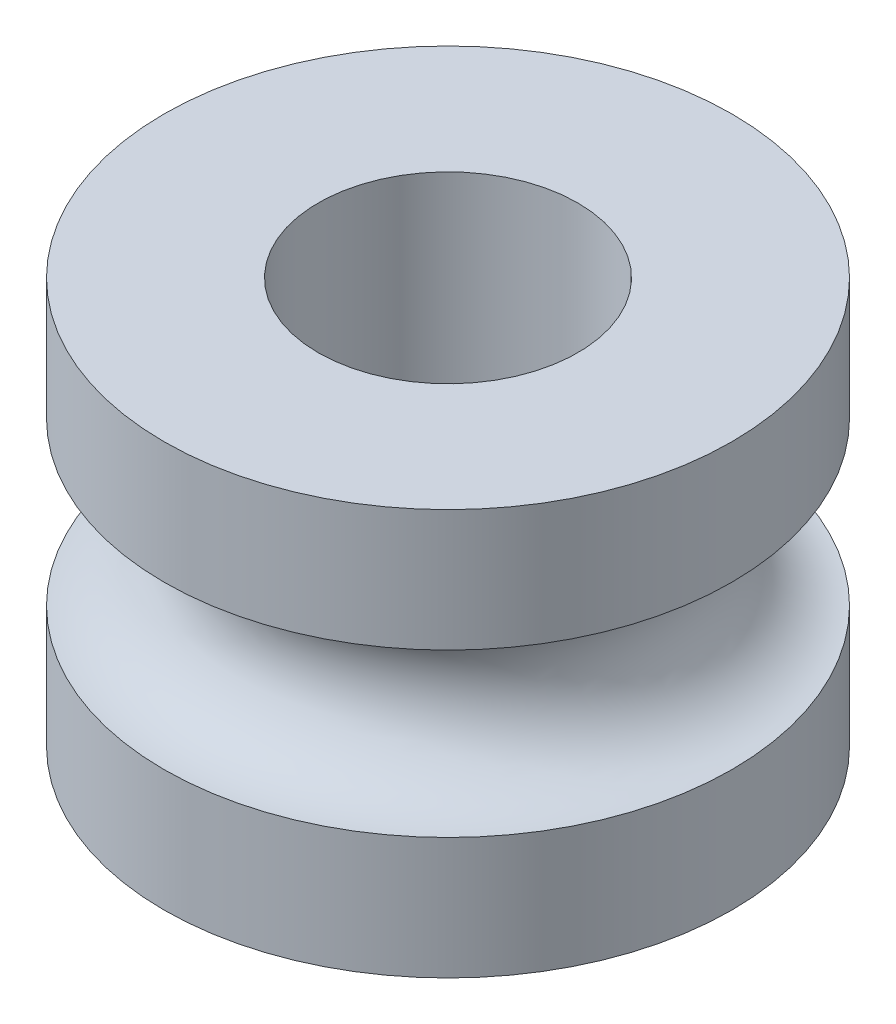
SolidWorks part; units mm, degrees
ref_plane "Front Plane" through (0, 0, 0) normal (0, 0, 1) x (1, 0, 0)
ref_plane "Top Plane" through (0, 0, 0) normal (0, 1, 0) x (1, 0, 0)
ref_plane "Right Plane" through (0, 0, 0) normal (1, 0, 0) x (0, 0, -1)
sketch "Sketch1" plane through (0, 0, 0) normal (0, 0, 1) x (1, 0, 0)
  line L0 (-1.6, 2.5) -> (-3.5, 2.5)
  line L1 (-3.5, 2.5) -> (-3.5, 1)
  line L2 (-3.5, -1) -> (-3.5, -2.5)
  line L3 (-3.5, -2.5) -> (-1.6, -2.5)
  line L4 (-1.6, -2.5) -> (-1.6, 2.5)
  arc A0 (-3.5, 1) -> (-3.5, -1) centre (-3.5, 0) cw
  dimension "D1" = 1
  dimension "D2" = 1.5
  dimension "D3" = 1.6
  dimension "D4" = 3.5
ref_axis "Axis1" through (0, 2.75, 0) along (0, -1, 0)
revolve "Revolve1" add sketch "Sketch1" angle 360 about axis through (0, 2.75, 0) along (0, -1, 0)
